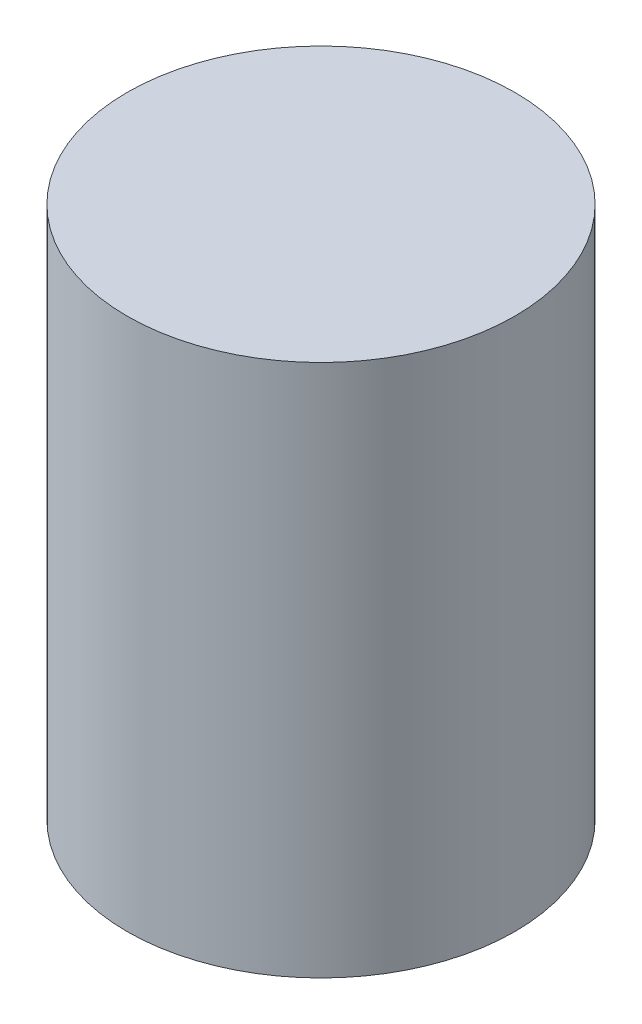
SolidWorks part; units mm, degrees
ref_plane "Front Plane" through (0, 0, 0) normal (0, 0, 1) x (1, 0, 0)
ref_plane "Top Plane" through (0, 0, 0) normal (0, 1, 0) x (1, 0, 0)
ref_plane "Right Plane" through (0, 0, 0) normal (1, 0, 0) x (0, 0, -1)
sketch "Sketch1" plane through (0, 0, 0) normal (0, 1, 0) x (1, 0, 0)
  circle A0 centre (0, 0) radius 18
  dimension "D1" = 36
extrude "Boss-Extrude1" add sketch "Sketch1" along normal blind 49.5
